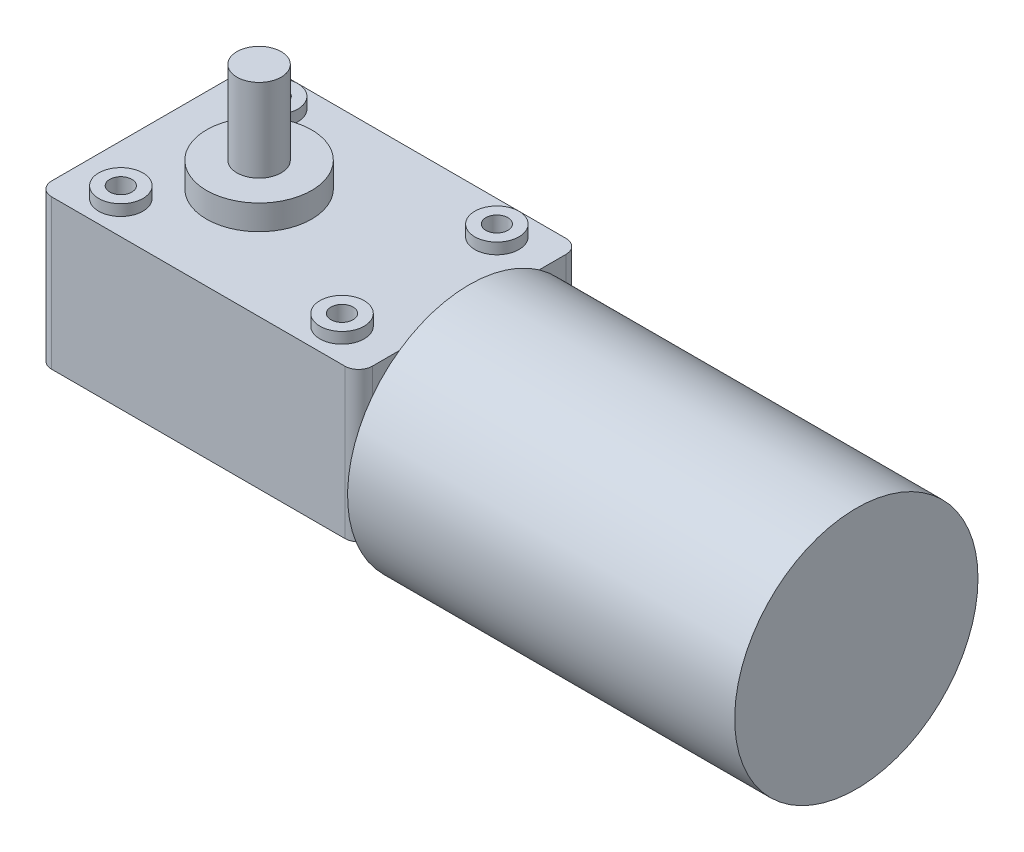
SolidWorks part; units mm, degrees
ref_plane "Front Plane" through (0, 0, 0) normal (0, 0, 1) x (1, 0, 0)
ref_plane "Top Plane" through (0, 0, 0) normal (0, 1, 0) x (1, 0, 0)
ref_plane "Right Plane" through (0, 0, 0) normal (1, 0, 0) x (0, 0, -1)
sketch "Sketch1" plane through (0, 0, 0) normal (0, 1, 0) x (1, 0, 0)
  line L1 (-26.5, -20) -> (26.5, -20)
  line L2 (-29, -17.5) -> (-29, 17.5)
  line L3 (-26.5, 20) -> (26.5, 20)
  line L4 (29, -17.5) -> (29, 17.5)
  line L5 (-29, -20) -> (29, 20) construction
  line L6 (-29, 20) -> (29, -20) construction
  arc A0 (-29, -17.5) -> (-26.5, -20) centre (-26.5, -17.5) ccw
  arc A1 (26.5, -20) -> (29, -17.5) centre (26.5, -17.5) ccw
  arc A2 (29, 17.5) -> (26.5, 20) centre (26.5, 17.5) ccw
  arc A3 (-29, 17.5) -> (-26.5, 20) centre (-26.5, 17.5) cw
  point P0 (0, 0)
  dimension "D3" = 2.5
  dimension "D1" = 58
  dimension "D2" = 40
extrude "Boss-Extrude1" add sketch "Sketch1" along normal mid plane 27
sketch "Sketch2" plane through (0, 13.5, 0) normal (0, 1, 0) x (1, 0, 0)
  line L0 (-1000, 0) -> (49000, 0) construction
  line L1 (-1000.4558, 14) -> (48999.5442, 14) construction
  line L2 (-1000.9116, -14) -> (48999.0884, -14) construction
  line L3 (-20, -994.0746) -> (-20, 49005.9254) construction
  line L4 (20, -995.2141) -> (20, 49004.7859) construction
  line L5 (-29, 17.5) -> (-29, -17.5) construction
  circle A0 centre (-20, 14) radius 4
  circle A1 centre (-20, -14) radius 4
  circle A2 centre (20, -14) radius 4
  circle A3 centre (20, 14) radius 4
  dimension "D5" = 8
  dimension "D6" = 8
  dimension "D7" = 8
  dimension "D8" = 8
  dimension "D1" = 14
  dimension "D2" = 14
  dimension "D3" = 9
  dimension "D4" = 40
extrude "Boss-Extrude2" add sketch "Sketch2" along normal blind 2
sketch "Sketch3" plane through (0, 15.5, 0) normal (0, 1, 0) x (1, 0, 0)
  circle A0 centre (-20, 14) radius 2
  circle A1 centre (20, 14) radius 2
  circle A2 centre (20, -14) radius 2
  circle A3 centre (-20, -14) radius 2
  dimension "D1" = 4
  dimension "D2" = 4
  dimension "D3" = 4
  dimension "D4" = 4
extrude "Cut-Extrude1" cut sketch "Sketch3" against normal blind 6
sketch "Sketch6" plane through (0, 13.5, 0) normal (0, 1, 0) x (1, 0, 0)
  line L0 (-1000, 0) -> (49000, 0) construction
  line L1 (-29, 17.5) -> (-29, -17.5) construction
  circle A0 centre (-9, 0) radius 9.5
  dimension "D1" = 19
  dimension "D2" = 20
extrude "Boss-Extrude5" add sketch "Sketch6" along normal blind 4.5
sketch "Sketch4" plane through (0, 18, 0) normal (0, 1, 0) x (1, 0, 0)
  circle A0 centre (-9, 0) radius 4
  circle A1 centre (-9, 0) radius 9.5 construction
  dimension "D1" = 8
extrude "Boss-Extrude3" add sketch "Sketch4" along normal blind 15
sketch "Sketch5" plane through (29, 0, 0) normal (1, 0, 0) x (0, 0, -1)
  line L0 (-17.5, 13.5) -> (17.5, 13.5) construction
  line L1 (0, -1000) -> (0, 49000) construction
  circle A0 centre (0, -4.5) radius 22
  dimension "D2" = 44
  dimension "D3" = 18
extrude "Boss-Extrude4" add sketch "Sketch5" along normal blind 70
mirror "Mirror2" about plane through (0, 0, 0) normal (0, 1, 0) of "Boss-Extrude5", "Cut-Extrude1", "Boss-Extrude2"
sketch "Sketch7" plane through (0, -18, 0) normal (0, -1, 0) x (1, 0, 0)
  circle A0 centre (-9, 0) radius 4
  dimension "D1" = 8
extrude "Cut-Extrude2" cut sketch "Sketch7" against normal blind 1.7
